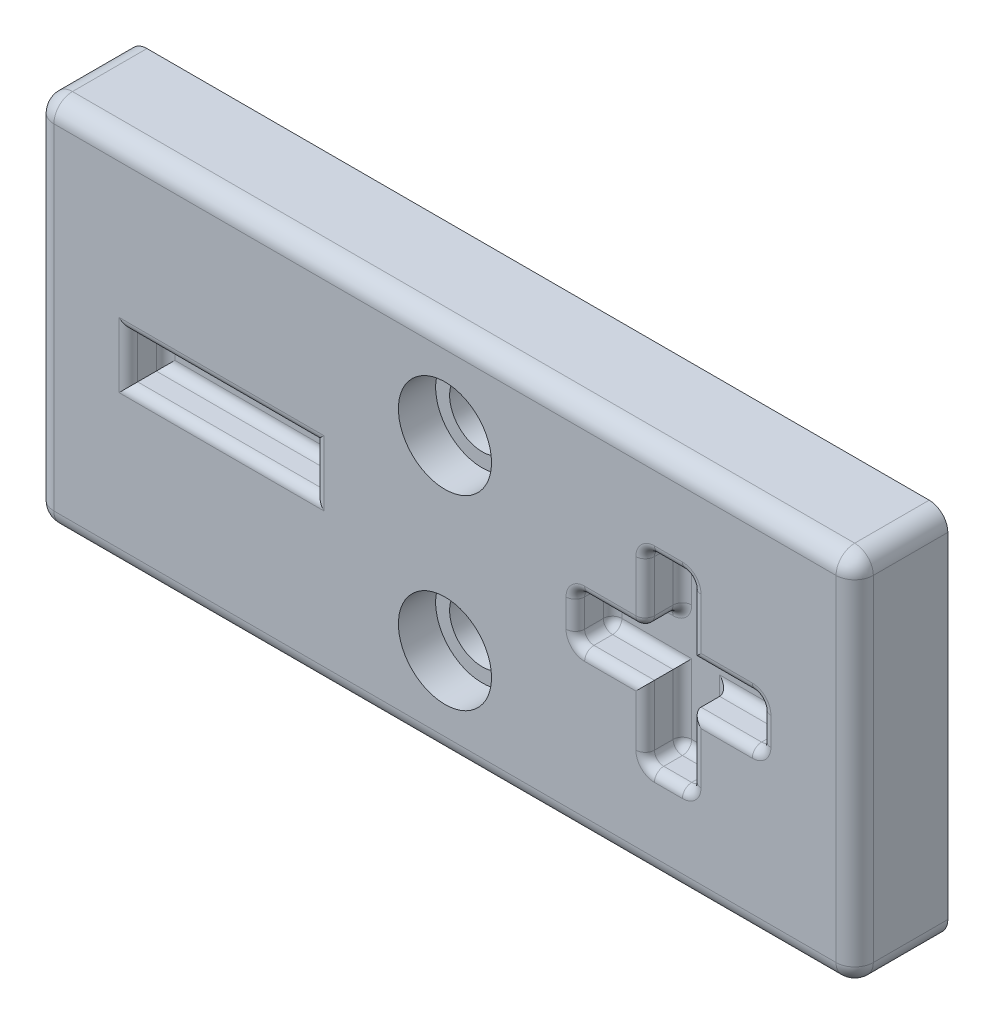
SolidWorks part; units mm, degrees
ref_plane "Front Plane" through (0, 0, 0) normal (0, 0, 1) x (1, 0, 0)
ref_plane "Top Plane" through (0, 0, 0) normal (0, 1, 0) x (1, 0, 0)
ref_plane "Right Plane" through (0, 0, 0) normal (1, 0, 0) x (0, 0, -1)
sketch "Sketch1" plane through (0, 0, 0) normal (0, 0, 1) x (1, 0, 0)
  line L0 (0, 0) -> (44, 0)
  line L1 (44, 0) -> (44, 20)
  line L2 (44, 20) -> (0, 20)
  line L3 (0, 20) -> (0, 0)
  dimension "D1" = 44
  dimension "D2" = 20
extrude "Boss-Extrude1" add sketch "Sketch1" along normal blind 5
sketch "Sketch2" plane through (0, 0, 5) normal (0, 0, 1) x (1, 0, 0)
  line L0 (44, 20) -> (0, 20) construction
  line L1 (0, 0) -> (44, 0) construction
  circle A0 centre (22, 15) radius 1.75
  circle A1 centre (22, 5) radius 1.75
  point P6 (22, 20)
  dimension "D1" = 3.5
  dimension "D2" = 3.5
  dimension "D3" = 5
  dimension "D4" = 5
extrude "Cut-Extrude1" cut sketch "Sketch2" against normal up to next
sketch "Sketch3" plane through (0, 0, 5) normal (0, 0, 1) x (1, 0, 0)
  circle A0 centre (22, 15) radius 2.5
  circle A1 centre (22, 5) radius 2.5
  dimension "D1" = 5
  dimension "D2" = 5
extrude "Cut-Extrude2" cut sketch "Sketch3" against normal blind 2
sketch "Sketch4" plane through (0, 0, 5) normal (0, 0, 1) x (1, 0, 0)
  line L0 (5, 11.25) -> (5, 8.75)
  line L1 (5, 8.75) -> (15, 8.75)
  line L2 (15, 8.75) -> (15, 11.25)
  line L3 (15, 11.25) -> (5, 11.25)
  line L4 (44, 20) -> (0, 20) construction
  line L5 (32.75, 5) -> (32.75, 8.75)
  line L6 (0, 20) -> (0, 0) construction
  line L7 (29, 11.25) -> (32.75, 11.25)
  line L8 (39, 11.25) -> (39, 8.75)
  line L9 (39, 8.75) -> (35.25, 8.75)
  line L10 (29, 8.75) -> (29, 11.25)
  line L11 (44, 0) -> (44, 20) construction
  line L12 (32.75, 15) -> (35.25, 15)
  line L13 (35.25, 15) -> (35.25, 11.25)
  line L14 (35.25, 5) -> (32.75, 5)
  line L15 (35.25, 11.25) -> (39, 11.25)
  line L16 (32.75, 8.75) -> (29, 8.75)
  line L17 (32.75, 11.25) -> (32.75, 15)
  line L18 (35.25, 8.75) -> (35.25, 5)
  dimension "D1" = 10
  dimension "D2" = 2.5
  dimension "D3" = 8.75
  dimension "D4" = 5
  dimension "D5" = 10
  dimension "D6" = 2.5
  dimension "D7" = 8.75
  dimension "D8" = 5
  dimension "D9" = 2.5
  dimension "D10" = 10
  dimension "D11" = 3.75
  dimension "D12" = 3.75
extrude "Cut-Extrude3" cut sketch "Sketch4" against normal blind 2
fillet "Fillet1" radius 1 8 edges at (22, 0, 5) (0, 10, 5) (22, 20, 5) (44, 10, 5) (44, 20, 2.5) (44, 0, 2.5) (0, 20, 2.5) (0, 0, 2.5)
fillet "Fillet2" radius 0.5 41 edges at (30.875, 8.75, 5) (32.75, 6.875, 5) (35.25, 6.875, 5) (37.125, 8.75, 5) (37.125, 11.25, 5) (35.25, 13.125, 5) (32.75, 13.125, 5) (29, 8.75, 4) (29, 10, 5) (32.75, 5, 4) (35.25, 5, 4) (34, 5, 5) (39, 8.75, 4) (39, 11.25, 4) (39, 10, 5) (35.25, 15, 4) (32.75, 15, 4) (34, 15, 5) (32.75, 11.25, 4) (29, 11.25, 4) (30.875, 11.25, 5) (30.875, 11.25, 3) (32.75, 13.125, 3) (34, 15, 3) (35.25, 13.125, 3) (37.125, 11.25, 3) (39, 10, 3) (37.125, 8.75, 3) (35.25, 6.875, 3) (34, 5, 3) (32.75, 6.875, 3) (30.875, 8.75, 3) (29, 10, 3) (15, 10, 3) (10, 8.75, 3) (5, 10, 3) (10, 11.25, 3) (5, 10, 5) (10, 8.75, 5) (15, 10, 5) (10, 11.25, 5)
